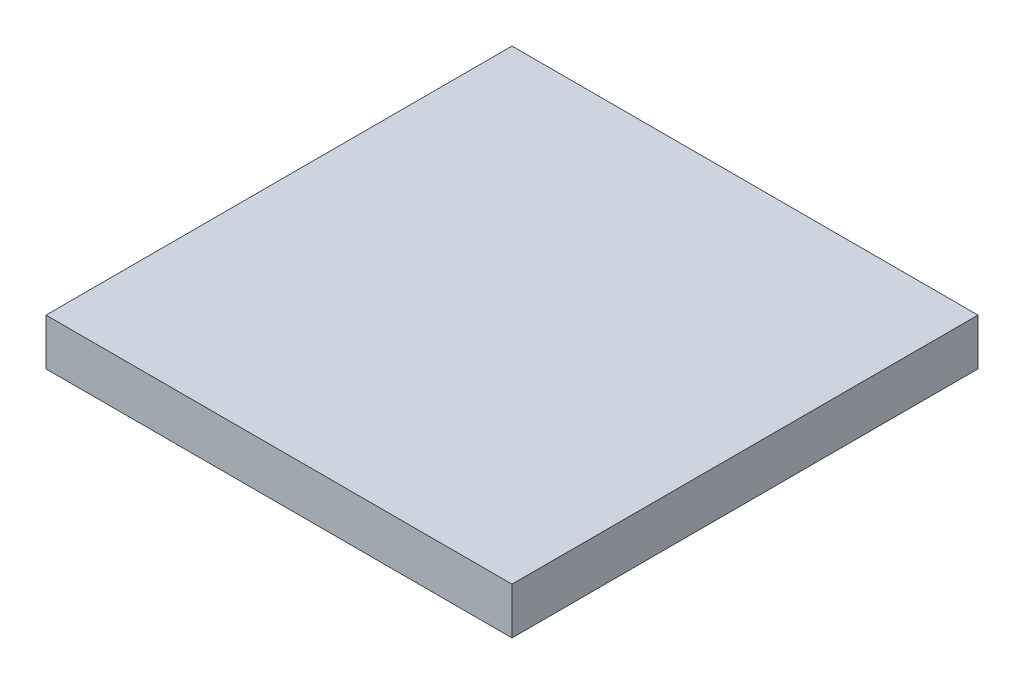
SolidWorks part; units mm, degrees
material "Бетон"
ref_plane "Front" through (0, 0, 0) normal (0, 0, 1) x (1, 0, 0)
ref_plane "Top" through (0, 0, 0) normal (0, 1, 0) x (1, 0, 0)
ref_plane "Right" through (0, 0, 0) normal (1, 0, 0) x (0, 0, -1)
sketch "Sketch1" plane through (0, 0, 0) normal (0, 1, 0) x (1, 0, 0)
  line L1 (0, 0) -> (1000, 0)
  line L2 (0, 0) -> (0, 1000)
  line L3 (0, 1000) -> (1000, 1000)
  line L4 (1000, 0) -> (1000, 1000)
  dimension "D1" = 1000
  dimension "D2" = 1000
extrude "Boss-Extrude1" add sketch "Sketch1" along normal blind 100
